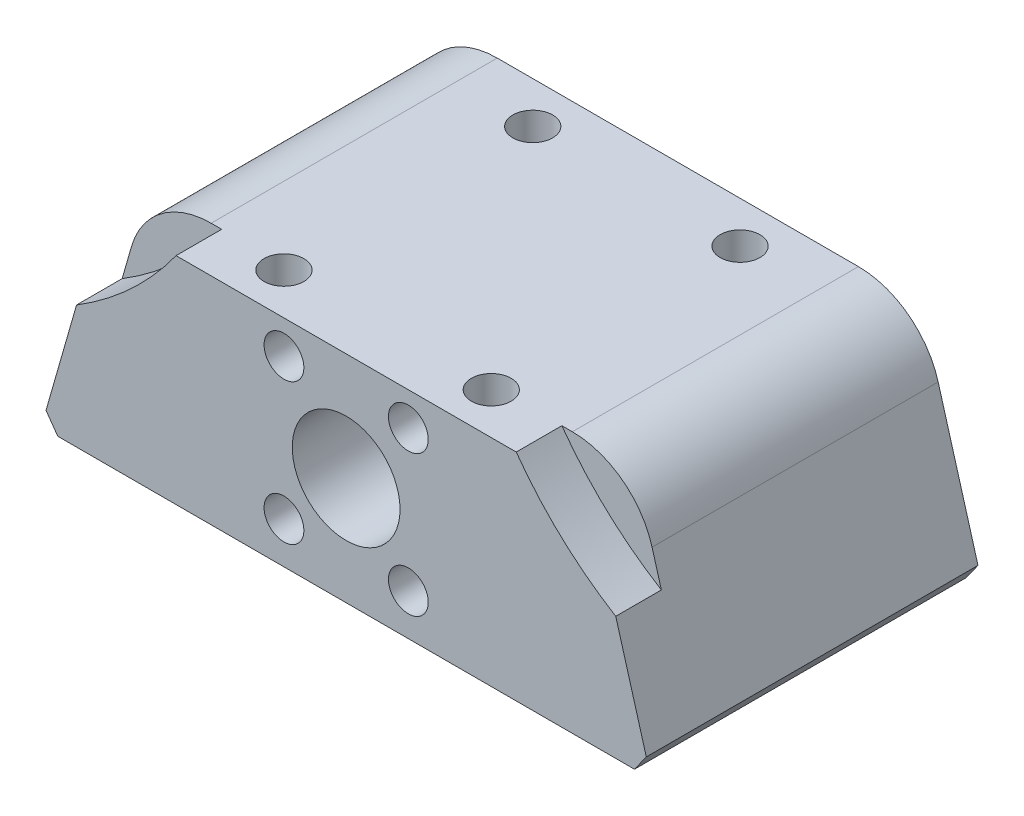
SolidWorks part; units mm, degrees
material "轻木"
ref_plane "前视基准面" through (0, 0, 0) normal (0, 0, 1) x (1, 0, 0)
ref_plane "上视基准面" through (0, 0, 0) normal (0, 1, 0) x (1, 0, 0)
ref_plane "右视基准面" through (0, 0, 0) normal (1, 0, 0) x (0, 0, -1)
sketch "草图1" plane through (0, 0, 0) normal (0, 0, 1) x (1, 0, 0)
  line L0 (-42.5, 45) -> (57.5, 45) construction
  line L1 (0, 0) -> (15, 0) construction
  line L2 (0, 0) -> (0, 17) construction
  line L3 (0, 17) -> (15, 17) construction
  line L4 (15, 0) -> (15, 17) construction
  line L9 (7.5, 21) -> (7.5, -5) construction
  line L10 (-29.2693, -5) -> (44.2693, -5)
  line L12 (-21.814, 21) -> (36.814, 21)
  line L14 (-21.814, 21) -> (-29.2693, -5)
  line L15 (36.814, 21) -> (44.2693, -5)
  circle A0 centre (15, 17) radius 2.4
  circle A1 centre (15, 0) radius 2.4
  circle A2 centre (0, 0) radius 2.4
  circle A3 centre (0, 17) radius 2.4
  circle A4 centre (-42.5, 45) radius 26.5 construction
  circle A5 centre (57.5, 45) radius 26.5 construction
  circle A6 centre (7.5, 8) radius 6.5
  point P23 (7.5, 17)
  dimension "D3" = 4.8
  dimension "D4" = 53
  dimension "D10" = 13
  dimension "D1" = 17
  dimension "D2" = 15
  dimension "D5" = 106
  dimension "D6" = 50
  dimension "D7" = 5
  dimension "D8" = 4
  dimension "D9" = 24
extrude "凸台-拉伸1" add sketch "草图1" along normal blind 40
fillet "圆角1" radius 10 2 edges at (36.814, 21, 20) (-21.814, 21, 20)
sketch "草图2" plane through (0, 21, 0) normal (0, 1, 0) x (1, 0, 0)
  line L0 (7.5, 0) -> (7.5, -40) construction
  line L1 (-5, -5) -> (20, -5) construction
  line L2 (-5, -5) -> (-5, -35) construction
  line L3 (-5, -35) -> (20, -35) construction
  line L4 (20, -5) -> (20, -35) construction
  line L5 (29.2784, 0) -> (-14.2784, 0) construction
  line L6 (29.2784, -40) -> (-14.2784, -40) construction
  circle A0 centre (-5, -5) radius 2.4
  circle A1 centre (20, -5) radius 2.4
  circle A2 centre (-5, -35) radius 2.4
  circle A3 centre (20, -35) radius 2.4
  point P10 (7.5, -5)
  dimension "D4" = 4.8
  dimension "D1" = 25
  dimension "D2" = 30
  dimension "D3" = 5
extrude "切除-拉伸1" cut sketch "草图2" against normal through all
sketch "草图4" plane through (0, 0, 40) normal (0, 0, 1) x (1, 0, 0)
  line L0 (-46.5, 45) -> (61.5, 45) construction
  line L1 (7.5, 8) -> (7.5, 45) construction
  line L2 (29.2784, 21) -> (-14.2784, 21) construction
  circle A0 centre (-46.5, 45) radius 41.2
  circle A1 centre (61.5, 45) radius 41.2
  point P5 (7.5, 45)
  dimension "D3" = 82.4
  dimension "D1" = 24
  dimension "D2" = 108
extrude "切除-拉伸2" cut sketch "草图4" against normal blind 5.5
sketch "草图5" plane through (0, 0, 0) normal (0, 0, -1) x (-1, 0, 0)
  line L0 (-42.2693, -5) -> (-44.2693, -5)
  line L1 (29.2693, -5) -> (-44.2693, -5) construction
  line L2 (-44.2693, -5) -> (-43.6958, -3)
  line L3 (-44.2693, -5) -> (-38.891, 13.7564) construction
  line L4 (-43.6958, -3) -> (-42.2693, -5)
  line L5 (-7.5, 21) -> (-7.5, -5) construction
  line L6 (-29.2784, 21) -> (14.2784, 21) construction
  line L7 (28.6958, -3) -> (27.2693, -5)
  line L8 (29.2693, -5) -> (28.6958, -3)
  line L9 (27.2693, -5) -> (29.2693, -5)
  dimension "D1" = 2
  dimension "D2" = 2
extrude "切除-拉伸3" cut sketch "草图5" against normal through all
